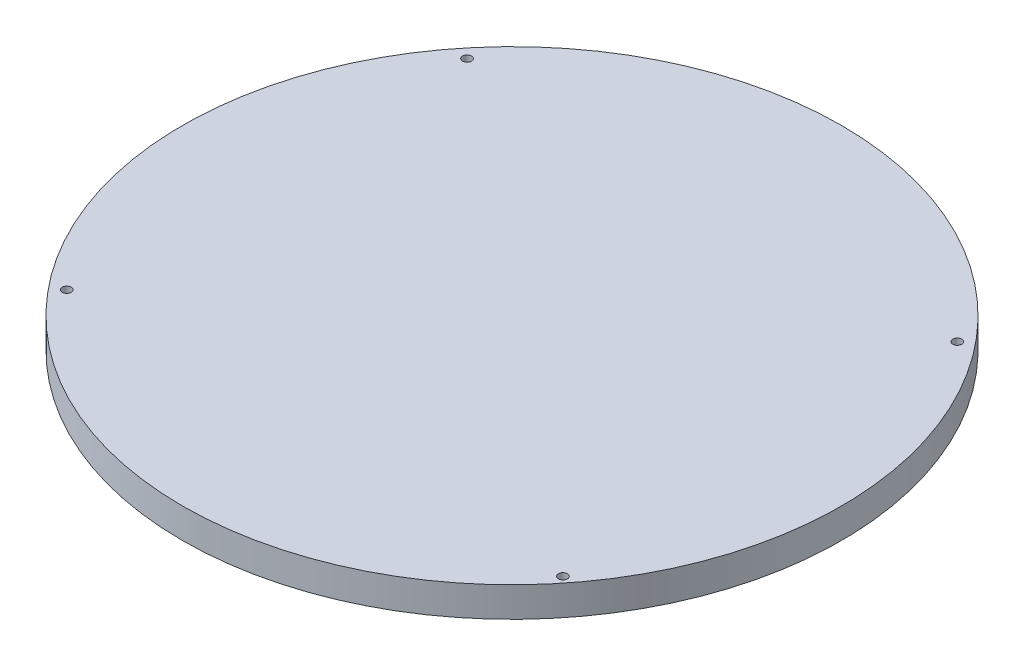
SolidWorks part; units mm, degrees
ref_plane "前视基准面" through (0, 0, 0) normal (0, 0, 1) x (1, 0, 0)
ref_plane "上视基准面" through (0, 0, 0) normal (0, 1, 0) x (1, 0, 0)
ref_plane "右视基准面" through (0, 0, 0) normal (1, 0, 0) x (0, 0, -1)
other "Configuration Table"
sketch "草图1" plane through (0, 0, 0) normal (0, 1, 0) x (1, 0, 0)
  circle A0 centre (0, 0) radius 110
  circle A1 centre (0, 0) radius 115
  circle A2 centre (-81.8198, 66.8198) radius 1.5
  circle A3 centre (-81.8198, -66.8198) radius 1.5
  circle A4 centre (83.8198, -66.8198) radius 1.5
  circle A5 centre (81.8198, 66.8198) radius 1.5
  point P5 (0, -110)
  point P32 (0.0184, -69.2688)
extrude "凸台-拉伸1" add sketch "草图1" along normal blind 10 contours A0 A5 A4 A3 A2
